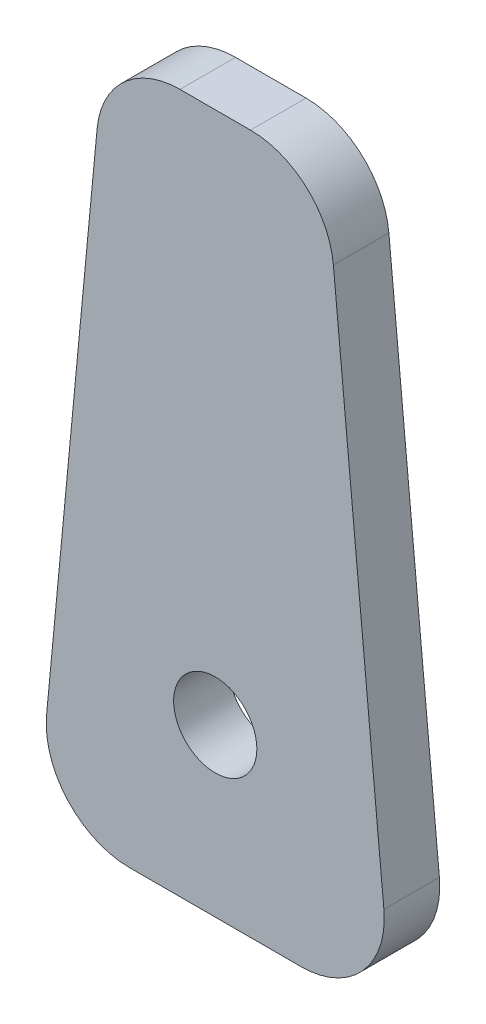
SolidWorks part; units mm, degrees
ref_plane "Front Plane" through (0, 0, 0) normal (0, 0, 1) x (1, 0, 0)
ref_plane "Top Plane" through (0, 0, 0) normal (0, 1, 0) x (1, 0, 0)
ref_plane "Right Plane" through (0, 0, 0) normal (1, 0, 0) x (0, 0, -1)
sketch "Sketch1" plane through (0, 0, 0) normal (0, 0, 1) x (1, 0, 0)
  line L1 (33.4618, 149.3571) -> (30.5715, 179.8371)
  line L2 (25.8303, 184.15) -> (21.7947, 184.15)
  line L3 (17.0535, 179.8371) -> (14.1632, 149.3571)
  line L4 (18.9044, 144.145) -> (28.7206, 144.145)
  arc A0 (21.7947, 184.15) -> (17.0535, 179.8371) centre (21.7947, 179.3875) ccw
  arc A1 (30.5715, 179.8371) -> (25.8303, 184.15) centre (25.8303, 179.3875) ccw
  arc A2 (28.7206, 144.145) -> (33.4618, 149.3571) centre (28.7206, 148.9075) ccw
  arc A3 (18.9044, 144.145) -> (14.1632, 149.3571) centre (18.9044, 148.9075) cw
  circle A4 centre (23.8125, 153.67) radius 2.3813
  point P4 (17.4625, 184.15)
  point P9 (30.1625, 184.15)
  dimension "D1" = 4.7625
  dimension "D2" = 12.7
  dimension "D7" = 9.525
extrude "Boss-Extrude1" add sketch "Sketch1" along normal blind 3.175
